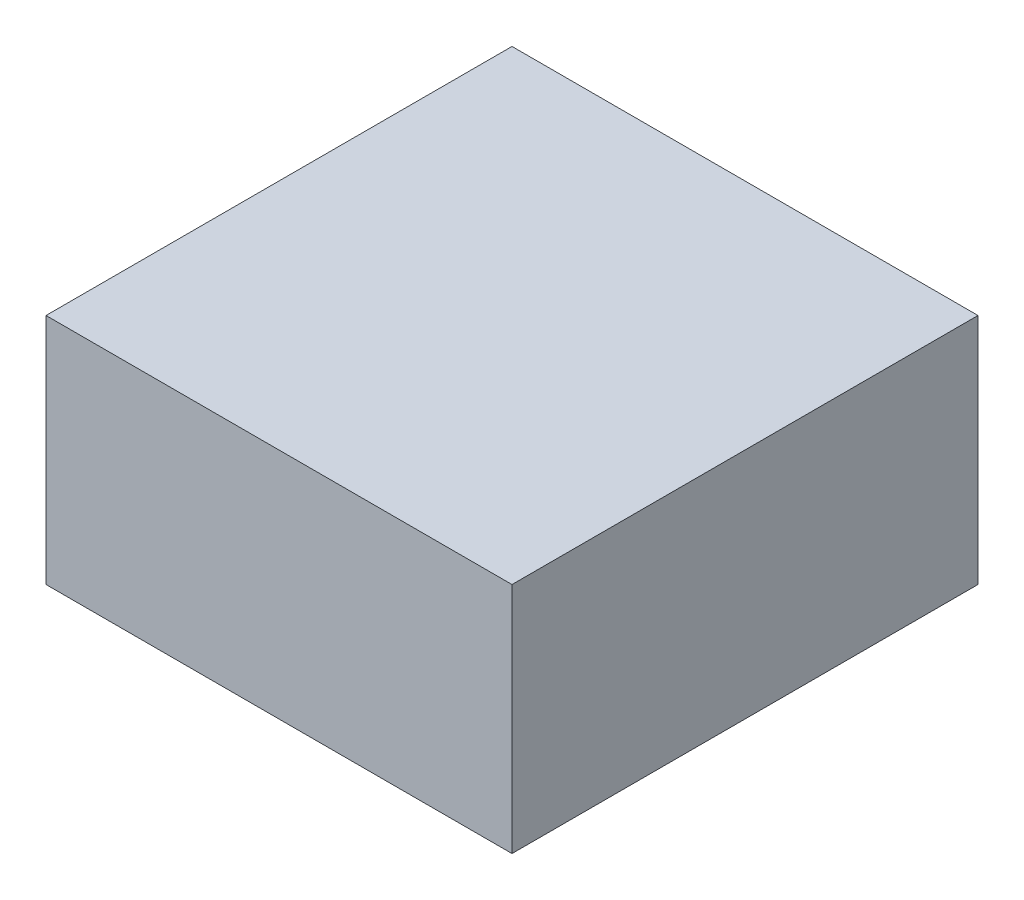
SolidWorks part; units mm, degrees
ref_plane "Front Plane" through (0, 0, 0) normal (0, 0, 1) x (1, 0, 0)
ref_plane "Top Plane" through (0, 0, 0) normal (0, 1, 0) x (1, 0, 0)
ref_plane "Right Plane" through (0, 0, 0) normal (1, 0, 0) x (0, 0, -1)
sketch "Sketch2" plane through (0, 0, 0) normal (0, 1, 0) x (1, 0, 0)
  line L1 (250, -250) -> (-250, -250)
  line L2 (250, -250) -> (250, 250)
  line L3 (250, 250) -> (-250, 250)
  line L4 (-250, -250) -> (-250, 250)
  line L5 (250, -250) -> (-250, 250) construction
  line L6 (250, 250) -> (-250, -250) construction
  point P0 (0, 0)
  dimension "D1" = 500
  dimension "D2" = 500
extrude "Boss-Extrude1" add sketch "Sketch2" along normal blind 250
